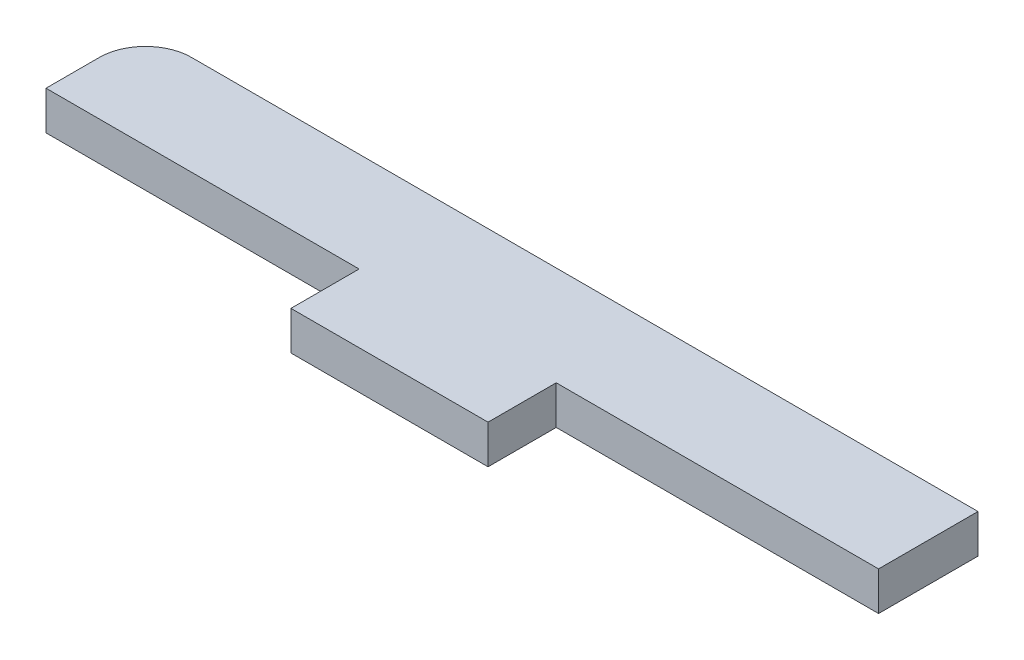
SolidWorks part; units mm, degrees
ref_plane "Front Plane" through (0, 0, 0) normal (0, 0, 1) x (1, 0, 0)
ref_plane "Top Plane" through (0, 0, 0) normal (0, 1, 0) x (1, 0, 0)
ref_plane "Right Plane" through (0, 0, 0) normal (1, 0, 0) x (0, 0, -1)
sketch "Sketch1" plane through (0, 0, 0) normal (0, 1, 0) x (1, 0, 0)
  line L1 (-431.0497, 194.9293) -> (-316.2417, 194.9293)
  line L2 (-431.0497, 194.9293) -> (-431.0497, 171.8153)
  line L3 (-431.0497, 171.8153) -> (-316.2417, 171.8153)
  line L4 (-316.2417, 194.9293) -> (-316.2417, 171.8153)
  dimension "D1" = 114.808
  dimension "D2" = 23.114
extrude "Boss-Extrude1" add sketch "Sketch1" along normal blind 5.334
fillet "Fillet1" radius 6.35 1 edges at (-431.0497, 2.667, -194.9293)
sketch "Sketch3" plane through (0, 5.334, 0) normal (0, 1, 0) x (1, 0, 0)
  line L0 (-431.0497, 171.8153) -> (-316.2417, 171.8153) construction
  line L1 (-387.8697, 181.217) -> (-431.0497, 181.217)
  line L2 (-387.8697, 181.217) -> (-387.8697, 171.8153)
  line L3 (-387.8697, 171.8153) -> (-431.0497, 171.8153)
  line L4 (-431.0497, 181.217) -> (-431.0497, 171.8153)
  line L5 (-360.6917, 181.217) -> (-316.2417, 181.217)
  line L6 (-360.6917, 181.217) -> (-360.6917, 171.8153)
  line L7 (-360.6917, 171.8153) -> (-316.2417, 171.8153)
  line L8 (-316.2417, 181.217) -> (-316.2417, 171.8153)
  line L9 (-387.8697, 181.217) -> (-360.6917, 181.217) construction
  dimension "D1" = 43.18
  dimension "D2" = 27.178
  dimension "D3" = 44.45
extrude "Cut-Extrude2" cut sketch "Sketch3" against normal through all
equation "\"MDF\"= .21in"
equation "\"Foamcore\"= .13in"
equation "\"Gmaterial\"= \"MDF\""
equation "\"D2@Sketch1\"=\"MDF\"+.7"
equation "\"D1@Boss-Extrude1\"=\"MDF\""
